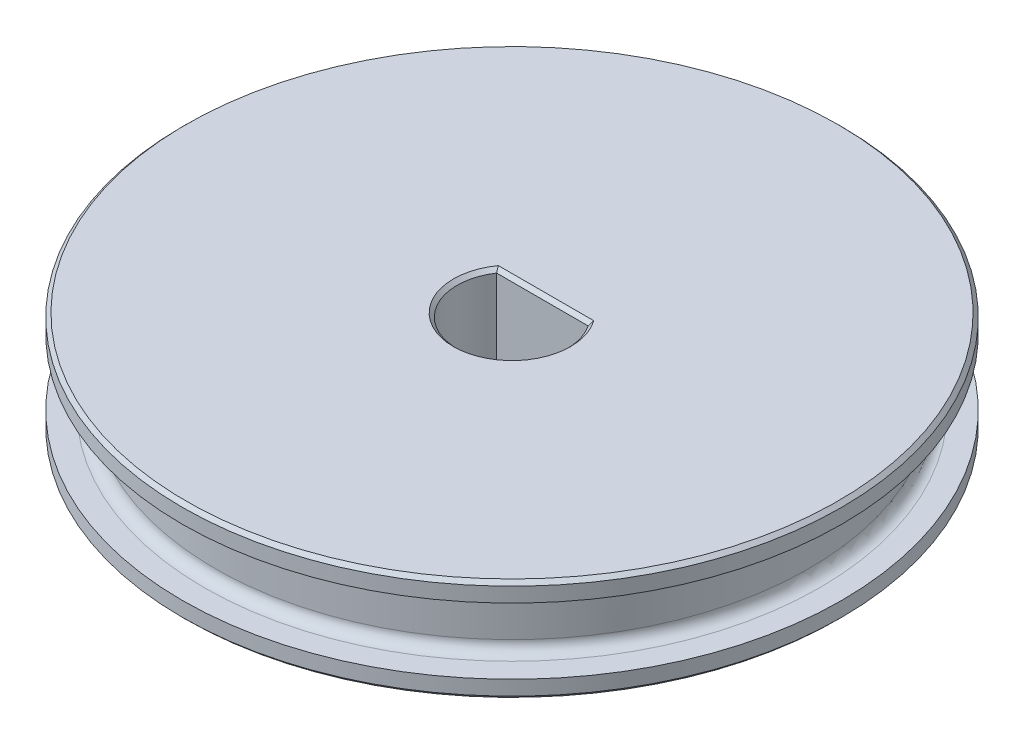
SolidWorks part; units mm, degrees
ref_plane "前视基准面" through (0, 0, 0) normal (0, 0, 1) x (1, 0, 0)
ref_plane "上视基准面" through (0, 0, 0) normal (0, 1, 0) x (1, 0, 0)
ref_plane "右视基准面" through (0, 0, 0) normal (1, 0, 0) x (0, 0, -1)
sketch "草图1" plane through (0, 0, 0) normal (1, 0, 0) x (0, 0, -1)
  line L0 (0, 0) -> (0, 5.6)
  line L1 (0, 5.6) -> (-18, 5.6)
  line L3 (-18, 0) -> (0, 0)
  line L4 (-18, 5.6) -> (-18, 4.6)
  line L5 (-18, 4.6) -> (-16.2, 4.6)
  line L6 (-16.2, 4.6) -> (-16.2, 1)
  line L7 (-16.2, 1) -> (-18, 1)
  line L8 (-18, 1) -> (-18, 0)
  dimension "D2" = 5.6
  dimension "D3" = 18
  dimension "D1" = 1
  dimension "D4" = 1.8
revolve "旋转2" add sketch "草图1" angle 360 about L0
sketch "草图2" plane through (0, 5.6, 0) normal (0, 1, 0) x (1, 0, 0)
  line L0 (-2.5, 1.6583) -> (2.5, 1.6583)
  circle A0 centre (0, 0) radius 3
  dimension "D1" = 6
  dimension "D2" = 5
extrude "切除-拉伸2" cut sketch "草图2" against normal through all contours L0 A0
fillet "圆角1" radius 0.6 2 edges at (0, 4.6, -16.2) (0, 1, -16.2)
chamfer "倒角1" distance 0.2 angle 45 4 edges at (0, 5.6, -1.6583) (0, 5.6, 3) (0, 0, 3) (0, 0, -1.6583)
chamfer "倒角2" distance 0.2 angle 45 2 edges at (0, 5.6, -18) (0, 0, -18)
